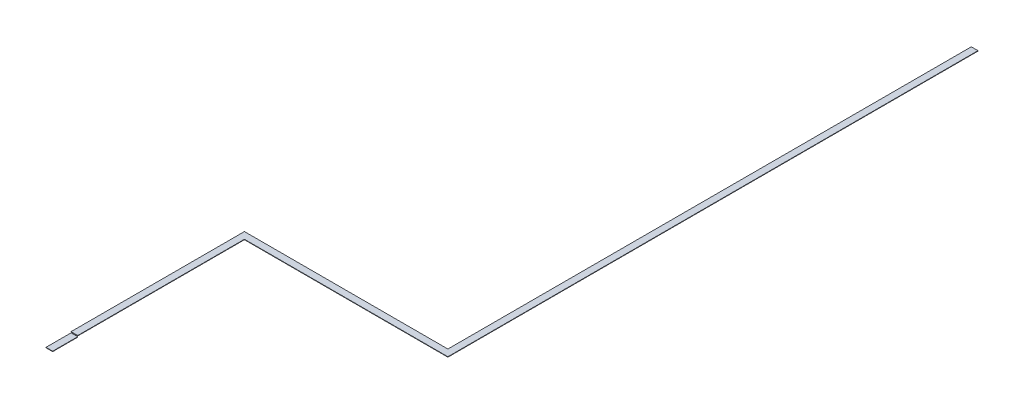
SolidWorks part; units mm, degrees
ref_plane "Front Plane" through (0, 0, 0) normal (0, 0, 1) x (1, 0, 0)
ref_plane "Top Plane" through (0, 0, 0) normal (0, 1, 0) x (1, 0, 0)
ref_plane "Right Plane" through (0, 0, 0) normal (1, 0, 0) x (0, 0, -1)
sketch "Sketch1" plane through (0, 0, 0) normal (0, 1, 0) x (1, 0, 0)
  line L5 (50.8, 1457.325) -> (1597.025, 1457.325) construction
  line L9 (0, 0) -> (0, 1508.125)
  line L11 (1546.225, 1508.125) -> (1546.225, 5486.4)
  line L13 (1597.025, 5486.4) -> (1597.025, 1457.325)
  line L14 (1597.025, 1457.325) -> (50.8, 1457.325)
  line L18 (50.8, 1457.325) -> (50.8, 0)
  line L20 (1546.225, 5486.4) -> (1597.025, 5486.4)
  line L27 (0, 1508.125) -> (1546.225, 1508.125)
  line L28 (50.8, 0) -> (0, 0)
  dimension "D1" = 5486.4
  dimension "D2" = 1546.225
  dimension "D3" = 1508.125
  dimension "D6" = 50.8
  dimension "D7" = 50.8
  dimension "D8" = 50.8
extrude "Boss-Extrude1" add sketch "Sketch1" along normal blind 3.175
sketch "Sketch2" plane through (0, 3.175, 0) normal (0, 1, 0) x (1, 0, 0)
  line L0 (50.8, 0) -> (50.8, 1457.325) construction
  line L1 (0, 0) -> (50.8, 0)
  line L2 (0, 0) -> (0, 190.5)
  line L3 (0, 190.5) -> (50.8, 190.5)
  line L4 (50.8, 0) -> (50.8, 190.5)
  dimension "D1" = 190.5
extrude "Cut-Extrude1" cut sketch "Sketch2" against normal through all
ref_plane "Plane1" [suppressed] through (0, 7.9375, 0) normal (0, 1, 0) x (1, 0, 0)
sketch "Sketch3" [suppressed] plane through (0, 7.9375, 0) normal (0, 1, 0) x (1, 0, 0)
  line L1 (0, 0) -> (50.8, 0)
  line L2 (0, 0) -> (0, 203.2)
  line L3 (0, 203.2) -> (50.8, 203.2)
  line L4 (50.8, 0) -> (50.8, 203.2)
extrude "Boss-Extrude2" [suppressed] add sketch "Sketch3" along normal blind 3.175 separate body
ref_plane "Plane2" through (0, -4.7625, 0) normal (0, -1, 0) x (-1, 0, 0)
sketch "Sketch4" plane through (0, -4.7625, 0) normal (0, -1, 0) x (-1, 0, 0)
  line L1 (0, 0) -> (-50.8, 0)
  line L2 (0, 0) -> (0, 190.5)
  line L3 (0, 190.5) -> (-50.8, 190.5)
  line L4 (-50.8, 0) -> (-50.8, 190.5)
extrude "Boss-Extrude3" add sketch "Sketch4" along normal blind 3.175 separate body
